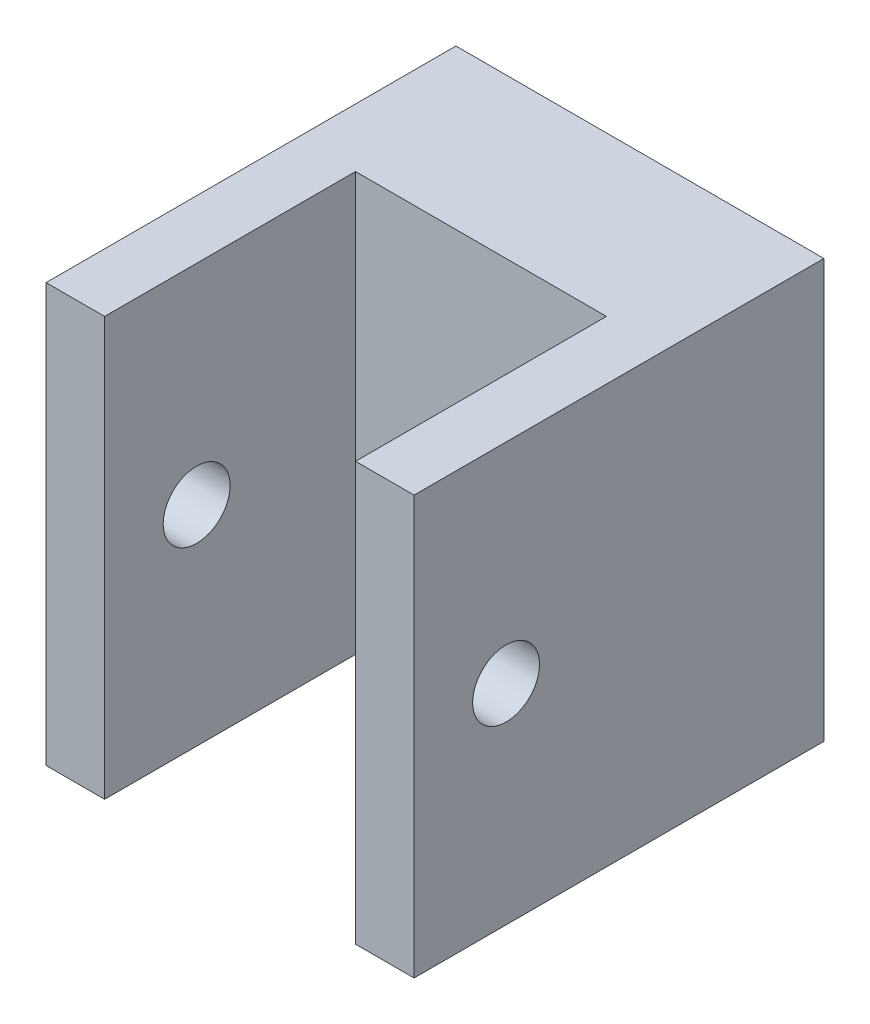
SolidWorks part; units mm, degrees
ref_plane "Front Plane" through (0, 0, 0) normal (0, 0, 1) x (1, 0, 0)
ref_plane "Top Plane" through (0, 0, 0) normal (0, 1, 0) x (1, 0, 0)
ref_plane "Right Plane" through (0, 0, 0) normal (1, 0, 0) x (0, 0, -1)
sketch "Sketch1" plane through (0, 0, 0) normal (0, 1, 0) x (1, 0, 0)
  line L1 (-15, 15) -> (15, 15)
  line L2 (-15, 15) -> (-15, -15)
  line L3 (-15, -15) -> (15, -15)
  line L4 (15, 15) -> (15, -15)
  line L5 (-15, 15) -> (15, -15) construction
  line L6 (-15, -15) -> (15, 15) construction
  line L7 (-15, -15) -> (-22, -15)
  line L8 (-15, -15) -> (-15, 22)
  line L9 (-15, 22) -> (-22, 22)
  line L10 (-22, -15) -> (-22, 22)
  line L11 (-15, 22) -> (22, 22)
  line L12 (-15, 22) -> (-15, 15)
  line L13 (-15, 15) -> (22, 15)
  line L14 (22, 22) -> (22, 15)
  line L15 (22, 15) -> (15, 15)
  line L16 (22, 15) -> (22, -15)
  line L17 (22, -15) -> (15, -15)
  line L18 (15, 15) -> (15, -15)
  point P0 (0, 0)
  dimension "D1" = 30
  dimension "D2" = 30
  dimension "D3" = 7
extrude "Boss-Extrude1" add sketch "Sketch1" along normal blind 50 contours L10 L7 L2 L8 L9 | L14 L11 L8 L1 L13 | L17 L16 L13 L4
sketch "Sketch2" plane through (0, 0, -22) normal (0, 0, -1) x (-1, 0, 0)
  line L0 (12.2218, 0) -> (12.2218, 35.179)
  line L1 (-22, 0) -> (22, 0) construction
  line L2 (2.2218, 0) -> (2.2218, 35.179)
  line L3 (-5.0782, 0) -> (-5.0782, 10.795)
  line L4 (-15.0782, 0) -> (-15.0782, 10.795)
  line L5 (0, 0) -> (0, 50) construction
  line L6 (-22, 50) -> (22, 50) construction
  line L7 (22, 25) -> (0, 25) construction
  line L8 (22, 50) -> (22, 0) construction
  line L9 (7.2218, 35.179) -> (-10.0782, 10.795) construction
  circle A1 centre (7.2218, 35.179) radius 5
  circle A2 centre (-10.0782, 10.795) radius 5
  line M8 (-22, 0) -> (22, 0)
  line M9 (22, 0) -> (22, 50)
  line M10 (22, 50) -> (-22, 50)
  line M11 (-22, 50) -> (-22, 0)
  dimension "D2" = 10
  dimension "D1" = 7.3
  dimension "D3" = 35.179
  dimension "D4" = 10.795
extrude "Boss-Extrude2" add sketch "Sketch2" along normal blind 6 contours A2 L3 L2 A1 L0 L4 M8 M9 M10 M11
sketch "Sketch3" plane through (0, 0, -28) normal (0, 0, -1) x (-1, 0, 0)
  line L0 (-7.0782, 10.795) -> (-7.0782, 0)
  line L1 (-13.0782, 10.795) -> (-13.0782, 0)
  line L2 (4.2218, 35.179) -> (4.2218, 0)
  line L3 (10.2218, 35.179) -> (10.2218, 0)
  line L4 (-22, 0) -> (-15.0782, 0) construction
  line L5 (-5.0782, 0) -> (2.2218, 0) construction
  line L6 (12.2218, 0) -> (22, 0) construction
  line L7 (-22, 0) -> (-13.0782, 0)
  line L8 (-22, 50) -> (22, 50)
  line L9 (-22, 50) -> (-22, 0)
  line L11 (22, 50) -> (22, 0)
  line L12 (-7.0782, 0) -> (4.2218, 0)
  line L13 (10.2218, 0) -> (22, 0)
  circle A0 centre (-10.0782, 10.795) radius 3 construction
  circle A1 centre (7.2218, 35.179) radius 3 construction
  arc A2 (-7.0782, 10.795) -> (-13.0782, 10.795) centre (-10.0782, 10.795) ccw
  arc A3 (10.2218, 35.179) -> (4.2218, 35.179) centre (7.2218, 35.179) ccw
  dimension "D1" = 6
  dimension "D2" = 3
extrude "Boss-Extrude3" add sketch "Sketch3" along normal blind 6
sketch "Sketch5" plane through (-22, 0, 0) normal (-1, 0, 0) x (0, 0, 1)
  line L0 (15, 50) -> (15, 0) construction
  line L1 (8, 25) -> (8, 0)
  line L2 (15, 0) -> (-34, 0) construction
  line L3 (0, 25) -> (0, 0)
  line L4 (4, 0) -> (4, 50) construction
  line L5 (15, 50) -> (-34, 50) construction
  circle A0 centre (4, 25) radius 4
  dimension "D2" = 8
  dimension "D1" = 11
extrude "Cut-Extrude1" cut sketch "Sketch5" against normal through all contours L4 A0 | A0 L4
